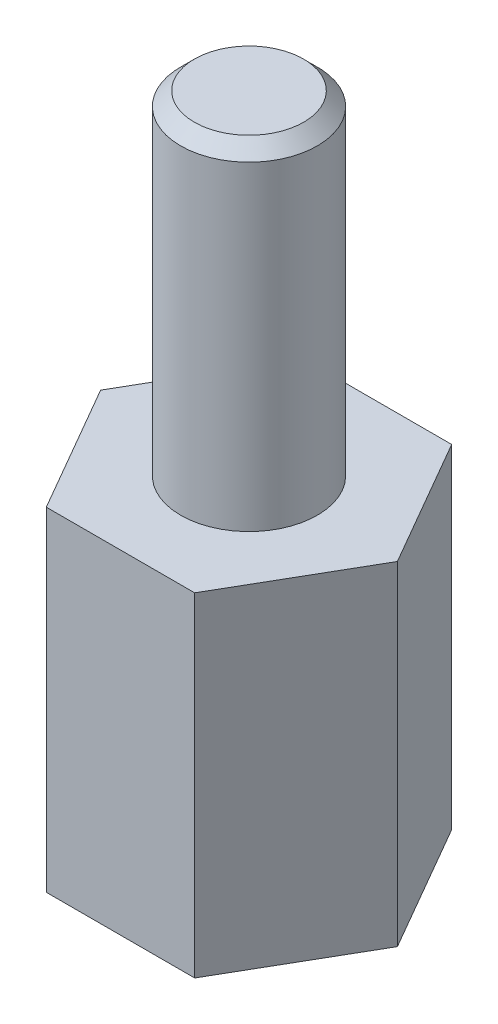
SolidWorks part; units mm, degrees
material "Nylon 101"
ref_plane "Front Plane" through (0, 0, 0) normal (0, 0, 1) x (1, 0, 0)
ref_plane "Top Plane" through (0, 0, 0) normal (0, 1, 0) x (1, 0, 0)
ref_plane "Right Plane" through (0, 0, 0) normal (1, 0, 0) x (0, 0, -1)
sketch "Sketch1" plane through (0, 0, 0) normal (0, 1, 0) x (1, 0, 0)
  line L1 (2.7135, 0) -> (1.3568, 2.35)
  line L2 (1.3568, 2.35) -> (-1.3568, 2.35)
  line L3 (-1.3568, 2.35) -> (-2.7135, 0)
  line L4 (-2.7135, 0) -> (-1.3568, -2.35)
  line L5 (-1.3568, -2.35) -> (1.3568, -2.35)
  line L6 (1.3568, -2.35) -> (2.7135, 0)
  circle A0 centre (0, 0) radius 2.35 construction
  dimension "D1" = 4.7
extrude "Boss-Extrude1" add sketch "Sketch1" along normal blind 6.1
sketch "Sketch2" plane through (0, 6.1, 0) normal (0, 1, 0) x (1, 0, 0)
  circle A0 centre (0, 0) radius 1.25
  dimension "D1" = 2.5
extrude "Boss-Extrude2" add sketch "Sketch2" along normal blind 6.1
chamfer "Chamfer1" distance 0.25 angle 45 1 edges at (0, 12.2, 1.25)
sketch "Sketch3" plane through (0, 0, 0) normal (0, -1, 0) x (1, 0, 0)
  circle A0 centre (0, 0) radius 1.25
  dimension "D1" = 2.5
extrude "Cut-Extrude1" cut sketch "Sketch3" against normal blind 5.5
